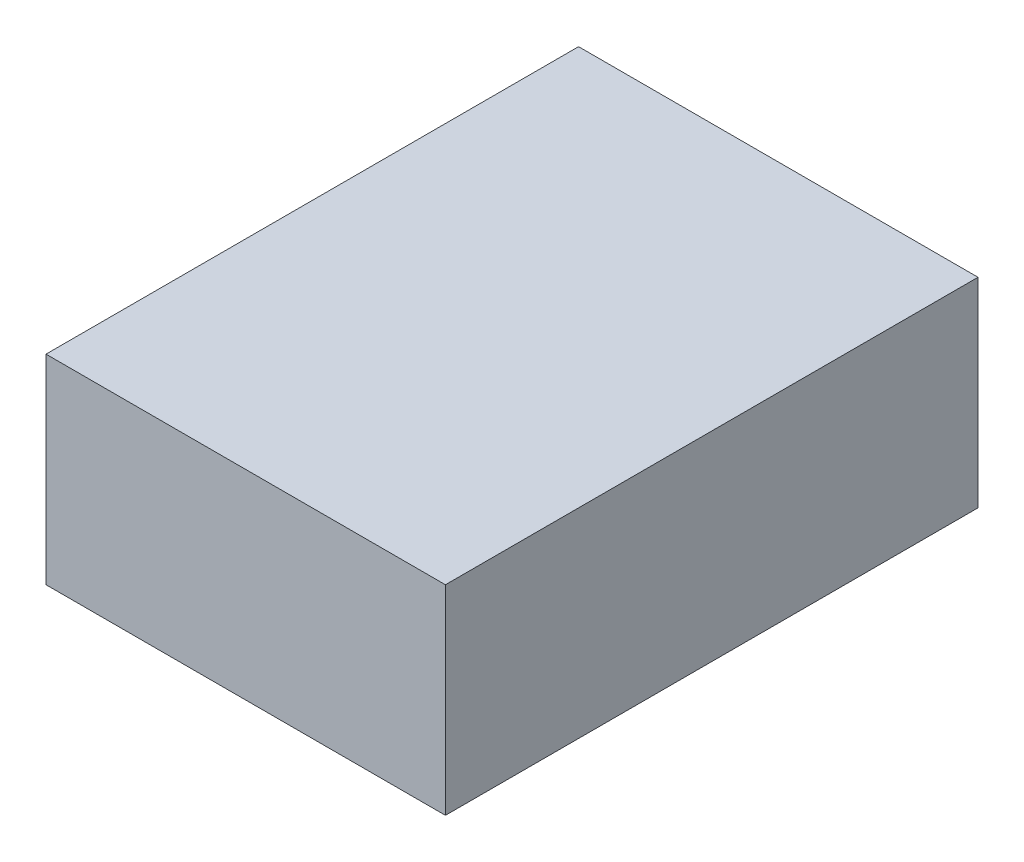
SolidWorks part; units mm, degrees
ref_plane "Front Plane" through (0, 0, 0) normal (0, 0, 1) x (1, 0, 0)
ref_plane "Top Plane" through (0, 0, 0) normal (0, 1, 0) x (1, 0, 0)
ref_plane "Right Plane" through (0, 0, 0) normal (1, 0, 0) x (0, 0, -1)
sketch "Sketch1" plane through (0, 0, 0) normal (0, 0, 1) x (1, 0, 0)
  line L1 (0, 0) -> (-30, 0)
  line L2 (0, 0) -> (0, 15)
  line L3 (0, 15) -> (-30, 15)
  line L4 (-30, 0) -> (-30, 15)
  dimension "D1" = 30
  dimension "D2" = 15
extrude "Boss-Extrude1" add sketch "Sketch1" along normal blind 40
